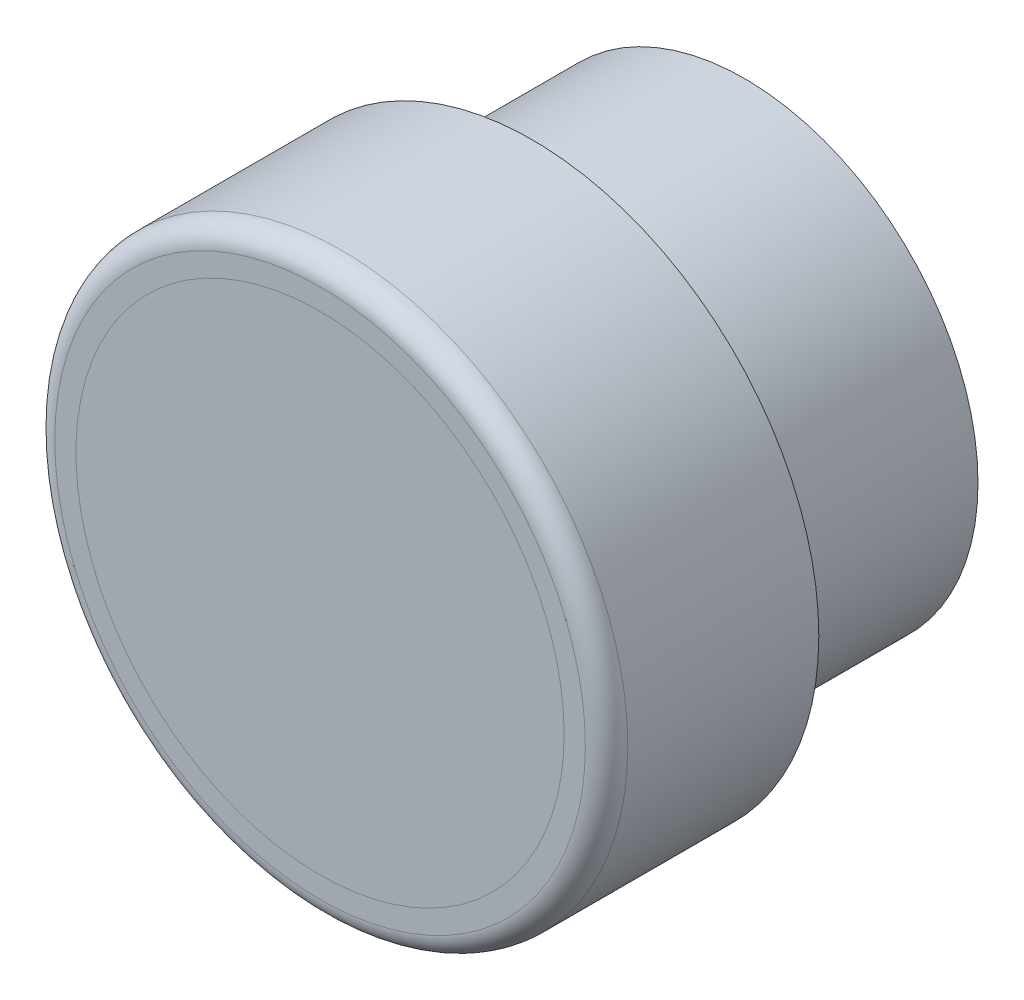
SolidWorks part; units mm, degrees
ref_plane "Front Plane" through (0, 0, 0) normal (0, 0, 1) x (1, 0, 0)
ref_plane "Top Plane" through (0, 0, 0) normal (0, 1, 0) x (1, 0, 0)
ref_plane "Right Plane" through (0, 0, 0) normal (1, 0, 0) x (0, 0, -1)
sketch "Sketch1" plane through (0, 0, 0) normal (0, 0, 1) x (1, 0, 0)
  circle A0 centre (0, 0) radius 11
  dimension "D1" = 22
extrude "Boss-Extrude1" add sketch "Sketch1" along normal blind 10
sketch "Sketch2" plane through (0, 0, 10) normal (0, 0, 1) x (1, 0, 0)
  circle A0 centre (0, 0) radius 13.5
  dimension "D1" = 27
extrude "Boss-Extrude2" add sketch "Sketch2" along normal blind 10
sketch "Sketch3" plane through (0, 0, 20) normal (0, 0, 1) x (1, 0, 0)
  circle A2 centre (0, 0) radius 11.5
  circle A3 centre (0, 0) radius 11.5
  dimension "D1" = 2
split line "Split Line1"
fillet "Fillet1" radius 1 1 edges at (13.5, 0, 20)
